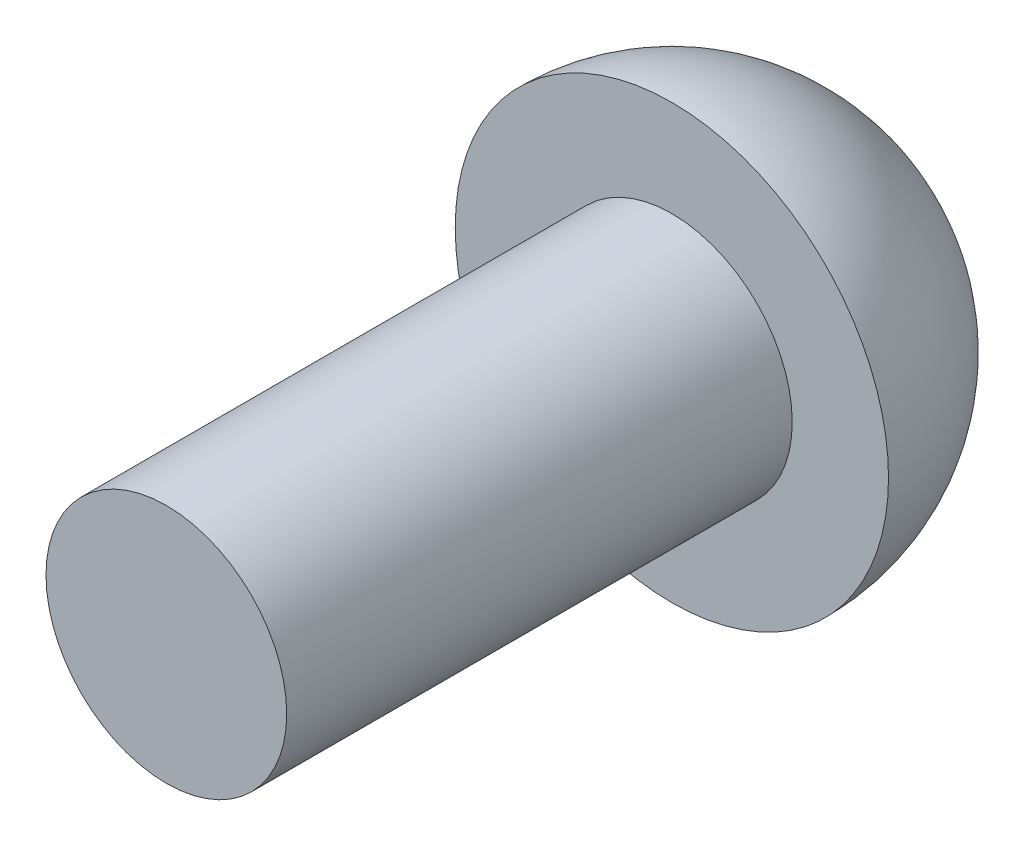
SolidWorks part; units mm, degrees
ref_plane "Front Plane" through (0, 0, 0) normal (0, 0, 1) x (1, 0, 0)
ref_plane "Top Plane" through (0, 0, 0) normal (0, 1, 0) x (1, 0, 0)
ref_plane "Right Plane" through (0, 0, 0) normal (1, 0, 0) x (0, 0, -1)
sketch "Sketch1" plane through (0, 0, 0) normal (0, 0, 1) x (1, 0, 0)
  line L0 (0, 9) -> (0, -9)
  arc A0 (0, 9) -> (0, -9) centre (0, 0) ccw
  dimension "D1" = 18
revolve "Revolve1" add sketch "Sketch1" angle 180 about L0
sketch "Sketch2" plane through (0, 0, 0) normal (0, 0, 1) x (1, 0, 0)
  circle A0 centre (0, 0) radius 5
  dimension "D1" = 10
extrude "Boss-Extrude1" add sketch "Sketch2" along normal blind 21
